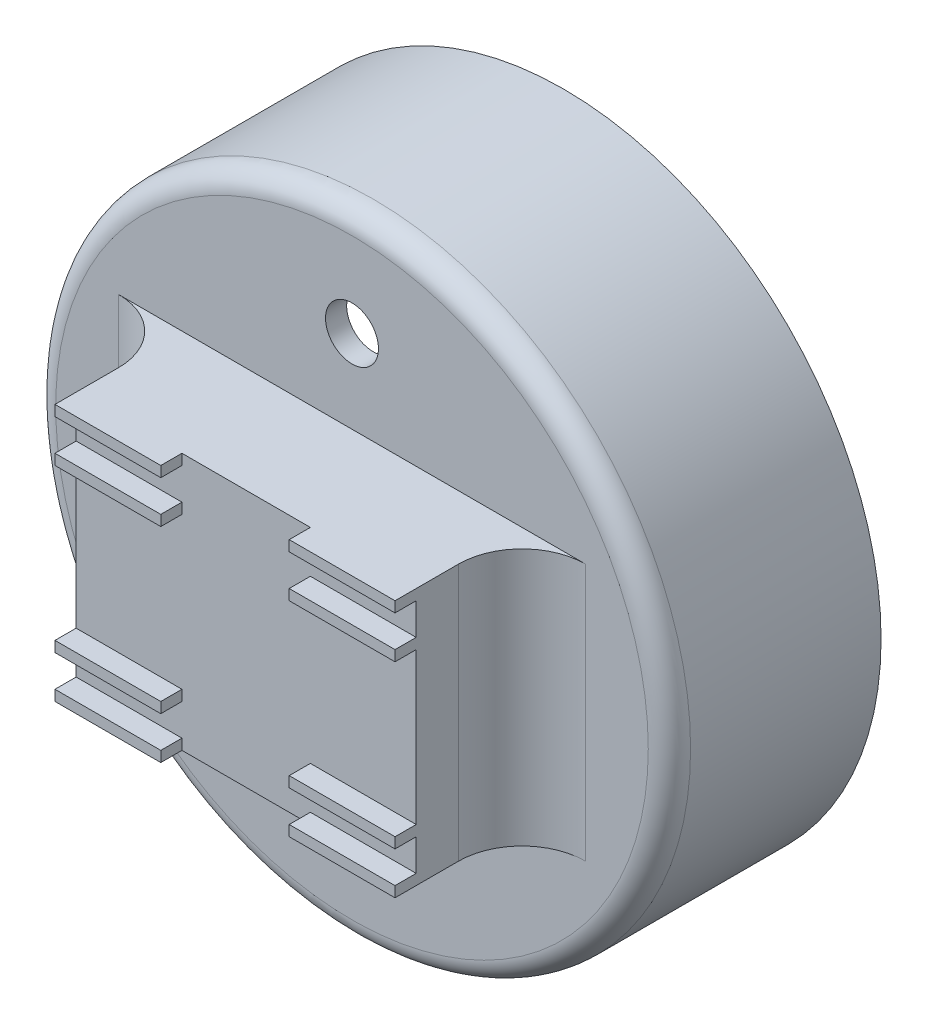
SolidWorks part; units mm, degrees
ref_plane "Front Plane" through (0, 0, 0) normal (0, 0, 1) x (1, 0, 0)
ref_plane "Top Plane" through (0, 0, 0) normal (0, 1, 0) x (1, 0, 0)
ref_plane "Right Plane" through (0, 0, 0) normal (1, 0, 0) x (0, 0, -1)
sketch "Sketch1" plane through (0, 0, 0) normal (0, 0, 1) x (1, 0, 0)
  circle A0 centre (0, 0) radius 38.1
  dimension "D1" = 76.2
extrude "Boss-Extrude1" add sketch "Sketch1" along normal blind 25.4 contours A0
shell "Shell1" thickness 2.54
fillet "Fillet1" radius 2.54 1 edges at (38.1, 0, 25.4)
sketch "Sketch2" plane through (0, 0, 25.4) normal (0, 0, 1) x (1, 0, 0)
  circle A0 centre (0, 25.4) radius 3.175
  dimension "D1" = 6.35
  dimension "D2" = 25.4
extrude "Cut-Extrude1" cut sketch "Sketch2" against normal through all
pattern_circular "CirPattern1" count 4 over 360 about axis through (0, 0, 0) along (0, 0, 1) of "Cut-Extrude1"
sketch "Sketch3" plane through (0, 0, 25.4) normal (0, 0, 1) x (1, 0, 0)
  line L1 (20.4062, -15.439) -> (-20.4062, -15.439)
  line L2 (20.4062, -15.439) -> (20.4062, 15.439)
  line L3 (20.4062, 15.439) -> (-20.4062, 15.439)
  line L4 (-20.4062, -15.439) -> (-20.4062, 15.439)
  line L5 (20.4062, -15.439) -> (-20.4062, 15.439) construction
  line L6 (20.4062, 15.439) -> (-20.4062, -15.439) construction
  circle A0 centre (25.4, 0) radius 3.175 construction
  circle A1 centre (-25.4, 0) radius 3.175 construction
  circle A2 centre (25.4, 0) radius 3.175
  circle A3 centre (-25.4, 0) radius 3.175
  point P0 (0, 0)
extrude "Boss-Extrude2" add sketch "Sketch3" along normal blind 12.7 contours L1 L4 L3 L2
sketch "Sketch6" plane through (0, 0, 25.4) normal (0, 0, 1) x (1, 0, 0)
  circle A0 centre (-25.4, 0) radius 3.175 construction
  circle A1 centre (0, 0) radius 35.56
  circle A2 centre (0, 0) radius 35.56
  circle A3 centre (-25.4, 0) radius 3.175
  circle A4 centre (25.4, 0) radius 3.175 construction
  circle A5 centre (25.4, 0) radius 3.175
  circle M2 centre (-25.4, 0) radius 3.175
  circle M4 centre (25.4, 0) radius 3.175
  dimension "D1" = 0
extrude "Boss-Extrude4" add sketch "Sketch6" against normal up to surface (2.54 mm away) contours M4 | M2 up to face at (-22.225, 0, 22.86)
fillet "Fillet3" radius 7.62 2 edges at (20.4062, 0, 25.4) (-20.4062, 0, 25.4)
sketch "Sketch8" plane through (0, 0, 38.1) normal (0, 0, 1) x (1, 0, 0)
  line L0 (-20.4062, -15.439) -> (-20.4062, 15.439) construction
  line L1 (-20.4062, 15.439) -> (20.4062, 15.439)
  line L2 (-20.4062, 15.439) -> (-20.4062, 14.169)
  line L3 (-20.4062, 14.169) -> (20.4062, 14.169)
  line L4 (20.4062, 15.439) -> (20.4062, 14.169)
  line L5 (20.4062, -15.439) -> (20.4062, 15.439) construction
  line L6 (20.4062, 0) -> (-20.4062, 0) construction
  line L7 (-20.4062, 12.264) -> (20.4062, 12.264) construction
  line L8 (20.4062, -15.439) -> (20.4062, 15.439) construction
  line L9 (20.4062, 9.089) -> (20.4062, 10.359)
  line L10 (-20.4062, 9.089) -> (-20.4062, 10.359)
  line L11 (-20.4062, 10.359) -> (20.4062, 10.359)
  line L12 (-20.4062, 9.089) -> (20.4062, 9.089)
  line L13 (-20.4062, -12.264) -> (20.4062, -12.264) construction
  line L14 (-20.4062, -9.089) -> (20.4062, -9.089)
  line L15 (-20.4062, -10.359) -> (20.4062, -10.359)
  line L16 (-20.4062, -9.089) -> (-20.4062, -10.359)
  line L17 (20.4062, -9.089) -> (20.4062, -10.359)
  line L18 (20.4062, -15.439) -> (20.4062, -14.169)
  line L19 (-20.4062, -14.169) -> (20.4062, -14.169)
  line L20 (-20.4062, -15.439) -> (-20.4062, -14.169)
  line L21 (-20.4062, -15.439) -> (20.4062, -15.439)
  line L22 (20.4062, 15.439) -> (-20.4062, 15.439) construction
  point P12 (0, 0)
  dimension "D1" = 1.27
  dimension "D2" = 1.905
  dimension "D3" = 0
extrude "Boss-Extrude7" add sketch "Sketch8" along normal blind 2.54
sketch "Sketch9" plane through (0, 0, 40.64) normal (0, 0, 1) x (1, 0, 0)
  line L0 (28.0262, 15.439) -> (-28.0262, 15.439) construction
  line L1 (-7.7062, 15.439) -> (7.7062, 15.439)
  line L2 (-7.7062, 15.439) -> (-7.7062, -15.439)
  line L3 (-7.7062, -15.439) -> (7.7062, -15.439)
  line L4 (7.7062, 15.439) -> (7.7062, -15.439)
  line L5 (28.0262, -15.439) -> (-28.0262, -15.439) construction
  line L6 (-20.4062, -9.089) -> (-20.4062, 9.089) construction
  line L7 (20.4062, -15.439) -> (20.4062, 15.439) construction
  dimension "D1" = 12.7
  dimension "D2" = 12.7
extrude "Cut-Extrude2" cut sketch "Sketch9" against normal up to surface (2.54 mm away) up to face at (0, 0, 38.1)
